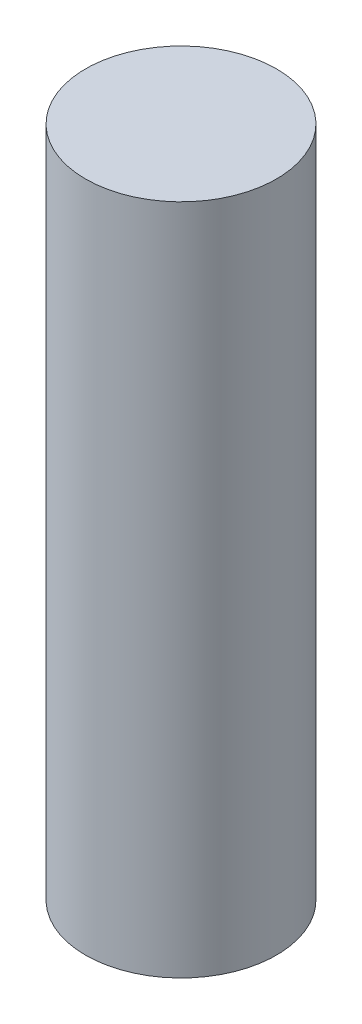
SolidWorks part; units mm, degrees
ref_plane "Plan de face" through (0, 0, 0) normal (0, 0, 1) x (1, 0, 0)
ref_plane "Plan de dessus" through (0, 0, 0) normal (0, 1, 0) x (1, 0, 0)
ref_plane "Plan de droite" through (0, 0, 0) normal (1, 0, 0) x (0, 0, -1)
sketch "Esquisse1" plane through (0, 0, 0) normal (0, 1, 0) x (1, 0, 0)
  circle A0 centre (0, 0) radius 7.1
  dimension "D1" = 14.2
extrude "Boss.-Extru.1" add sketch "Esquisse1" along normal blind 50
